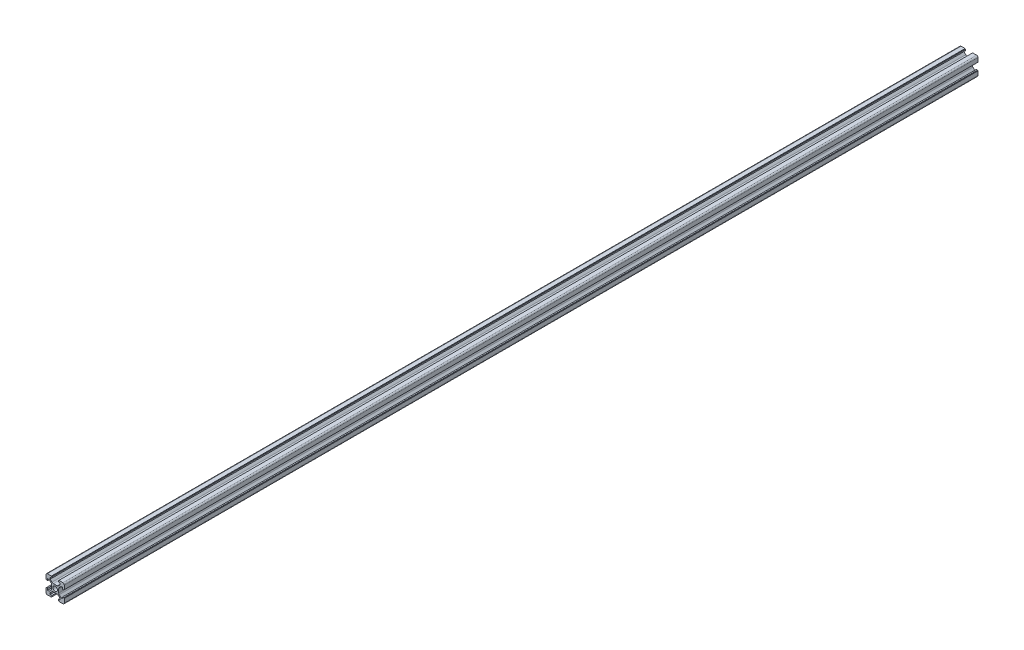
SolidWorks part; units mm, degrees
ref_plane "Front Plane" through (0, 0, 0) normal (0, 0, 1) x (1, 0, 0)
ref_plane "Top Plane" through (0, 0, 0) normal (0, 1, 0) x (1, 0, 0)
ref_plane "Right Plane" through (0, 0, 0) normal (1, 0, 0) x (0, 0, -1)
sketch "Sketch1" plane through (0, 0, 0) normal (0, 0, 1) x (1, 0, 0)
  line L0 (10, -4.1) -> (10, -8.5)
  line L1 (4.1, 10) -> (8.5, 10)
  line L2 (8.5, -10) -> (4.1, -10)
  line L3 (-8.5, -10) -> (-4.1, -10)
  line L4 (10, 8.5) -> (10, 4.1)
  line L7 (8.5, 10) -> (4.1, 10)
  line L8 (5.5, 6.5607) -> (3.4251, 4.4858)
  line L9 (8.5, 10) -> (4.1, 10)
  line L10 (3.9, 2.0109) -> (3.9, -2.0109)
  line L11 (2.0109, -3.9) -> (-2.0109, -3.9)
  line L12 (-3.9, -2.0109) -> (-3.9, 2.0109)
  line L13 (-2.0109, 3.9) -> (2.8393, 3.9)
  line L14 (2.5, 0) -> (22.2403, 0) construction
  line L15 (3.6, 9.5) -> (3.6, 8.2)
  line L16 (9.5, 3.6) -> (8.2, 3.6)
  line L17 (8.2, 3.6) -> (8.2, 5.5)
  line L18 (8.2, 5.5) -> (6.5607, 5.5)
  line L19 (10, -4.1) -> (10, -8.5)
  line L20 (4.1, 9.5) -> (3.6, 9.5)
  line L21 (4.1, 10) -> (4.1, 9.5)
  line L22 (8.5, 10) -> (4.1, 10)
  line L23 (10, 4.1) -> (9.5, 4.1)
  line L24 (9.5, 4.1) -> (9.5, 3.6)
  line L25 (5.5, 8.2) -> (5.5, 6.5607)
  line L26 (3.6, 8.2) -> (5.5, 8.2)
  line L27 (4.4858, 3.4251) -> (6.5607, 5.5)
  line L28 (10, -8.5) -> (10, -4.1)
  line L29 (6.5607, -5.5) -> (4.4858, -3.4251)
  line L30 (10, -8.5) -> (10, -4.1)
  line L31 (2.0109, -3.9) -> (-2.0109, -3.9)
  line L32 (3.9, 2.8393) -> (3.9, -2.0109)
  line L33 (9.5, -3.6) -> (8.2, -3.6)
  line L34 (3.6, -9.5) -> (3.6, -8.2)
  line L35 (3.6, -8.2) -> (5.5, -8.2)
  line L36 (5.5, -8.2) -> (5.5, -6.5607)
  line L37 (9.5, -4.1) -> (9.5, -3.6)
  line L38 (10, -4.1) -> (9.5, -4.1)
  line L39 (10, -8.5) -> (10, -4.1)
  line L40 (4.1, -10) -> (4.1, -9.5)
  line L41 (4.1, -9.5) -> (3.6, -9.5)
  line L42 (8.2, -5.5) -> (6.5607, -5.5)
  line L43 (8.2, -3.6) -> (8.2, -5.5)
  line L44 (3.4251, -4.4858) -> (5.5, -6.5607)
  line L45 (-4.1, -10) -> (-8.5, -10)
  line L46 (-10, -8.5) -> (-10, -4.1)
  line L47 (-8.5, -10) -> (-4.1, -10)
  line L48 (-5.5, -6.5607) -> (-3.4251, -4.4858)
  line L49 (-8.5, -10) -> (-4.1, -10)
  line L50 (-3.9, -2.0109) -> (-3.9, 2.0109)
  line L51 (2.0109, -3.9) -> (-2.0109, -3.9)
  line L52 (-3.6, -9.5) -> (-3.6, -8.2)
  line L53 (-9.5, -3.6) -> (-8.2, -3.6)
  line L54 (-8.2, -3.6) -> (-8.2, -5.5)
  line L55 (-8.2, -5.5) -> (-6.5607, -5.5)
  line L56 (-4.1, -9.5) -> (-3.6, -9.5)
  line L57 (-4.1, -10) -> (-4.1, -9.5)
  line L58 (-8.5, -10) -> (-4.1, -10)
  line L59 (-10, -4.1) -> (-9.5, -4.1)
  line L60 (-9.5, -4.1) -> (-9.5, -3.6)
  line L61 (-5.5, -8.2) -> (-5.5, -6.5607)
  line L62 (-3.6, -8.2) -> (-5.5, -8.2)
  line L63 (-4.4858, -3.4251) -> (-6.5607, -5.5)
  line L64 (-10, 4.1) -> (-10, 8.5)
  line L65 (-8.5, 10) -> (-4.1, 10)
  line L66 (-10, 8.5) -> (-10, 4.1)
  line L67 (-6.5607, 5.5) -> (-4.4858, 3.4251)
  line L68 (-10, 8.5) -> (-10, 4.1)
  line L69 (-2.0109, 3.9) -> (2.0109, 3.9)
  line L70 (-3.9, -2.0109) -> (-3.9, 2.0109)
  line L71 (-9.5, 3.6) -> (-8.2, 3.6)
  line L72 (-3.6, 9.5) -> (-3.6, 8.2)
  line L73 (-3.6, 8.2) -> (-5.5, 8.2)
  line L74 (-5.5, 8.2) -> (-5.5, 6.5607)
  line L75 (-9.5, 4.1) -> (-9.5, 3.6)
  line L76 (-10, 4.1) -> (-9.5, 4.1)
  line L77 (-10, 8.5) -> (-10, 4.1)
  line L78 (-4.1, 10) -> (-4.1, 9.5)
  line L79 (-4.1, 9.5) -> (-3.6, 9.5)
  line L80 (-8.2, 5.5) -> (-6.5607, 5.5)
  line L81 (-8.2, 3.6) -> (-8.2, 5.5)
  line L82 (-3.4251, 4.4858) -> (-5.5, 6.5607)
  line L83 (4.1, -10) -> (8.5, -10)
  arc A0 (2.0109, -3.9) -> (3.4251, -4.4858) centre (2.0109, -5.9) cw
  arc A1 (4.4858, -3.4251) -> (3.9, -2.0109) centre (5.9, -2.0109) cw
  arc A2 (3.9, 2.0109) -> (4.4858, 3.4251) centre (5.9, 2.0109) cw
  arc A3 (2.0109, 3.9) -> (3.4251, 4.4858) centre (2.0109, 5.9) ccw
  arc A4 (-2.0109, 3.9) -> (-3.4251, 4.4858) centre (-2.0109, 5.9) cw
  arc A5 (-4.4858, 3.4251) -> (-3.9, 2.0109) centre (-5.9, 2.0109) cw
  arc A6 (-3.4251, -4.4858) -> (-2.0109, -3.9) centre (-2.0109, -5.9) cw
  arc A7 (-3.9, -2.0109) -> (-4.4858, -3.4251) centre (-5.9, -2.0109) cw
  circle A8 centre (0, 0) radius 2.5
  arc A9 (-8.5, -10) -> (-10, -8.5) centre (-8.5, -8.5) cw
  arc A10 (-10, 8.5) -> (-8.5, 10) centre (-8.5, 8.5) cw
  arc A11 (8.5, 10) -> (10, 8.5) centre (8.5, 8.5) cw
  arc A12 (8.5, -10) -> (10, -8.5) centre (8.5, -8.5) ccw
  point P0 (0, 0)
  point P86 (0, 0)
  point P107 (10, -10)
  dimension "D3" = 2
  dimension "D5" = 5
  dimension "D2" = 1.5
  dimension "D8" = 1.5
  dimension "D4" = 6.1
  dimension "D6" = 20
  dimension "D7" = 6.1
  dimension "D9" = 20
  dimension "D11" = 0.5
  dimension "D12" = 0.5
extrude "Boss-Extrude2" add sketch "Sketch1" along normal blind 1000
